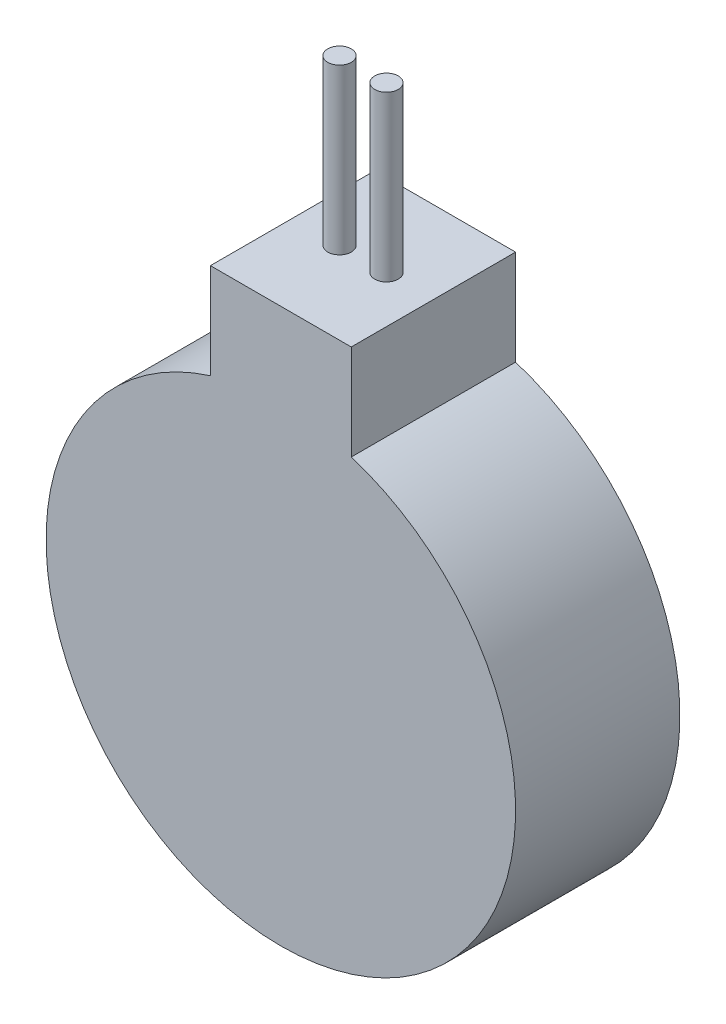
SolidWorks part; units mm, degrees
ref_plane "Front Plane" through (0, 0, 0) normal (0, 0, 1) x (1, 0, 0)
ref_plane "Top Plane" through (0, 0, 0) normal (0, 1, 0) x (1, 0, 0)
ref_plane "Right Plane" through (0, 0, 0) normal (1, 0, 0) x (0, 0, -1)
sketch "Sketch1" plane through (0, 0, 0) normal (0, 0, 1) x (1, 0, 0)
  line L0 (0, 6.8) -> (0, 0) construction
  line L2 (-1.5, 4.7697) -> (-1.5, 6.8)
  line L3 (-1.5, 6.8) -> (1.5, 6.8)
  line L4 (1.5, 4.7697) -> (1.5, 6.8)
  arc A0 (-1.5, 4.7697) -> (1.5, 4.7697) centre (0, 0) ccw
  dimension "D1" = 5
  dimension "D2" = 6.8
  dimension "D3" = 3
extrude "Boss-Extrude1" add sketch "Sketch1" along normal blind 3.5
sketch "Sketch2" plane through (0, 6.8, 0) normal (0, 1, 0) x (1, 0, 0)
  line L0 (-1.5, -1.75) -> (-0.5, -1.75) construction
  line L1 (-1.5, -3.5) -> (-1.5, 0) construction
  line L2 (-0.5, -1.75) -> (0.5, -1.75) construction
  line L3 (0.5, -1.75) -> (1.5, -1.75) construction
  line L4 (1.5, -3.5) -> (1.5, 0) construction
  circle A0 centre (-0.5, -1.75) radius 0.25
  circle A1 centre (0.5, -1.75) radius 0.25
  dimension "D1" = 0.5
extrude "Boss-Extrude2" add sketch "Sketch2" along normal blind 3.5
